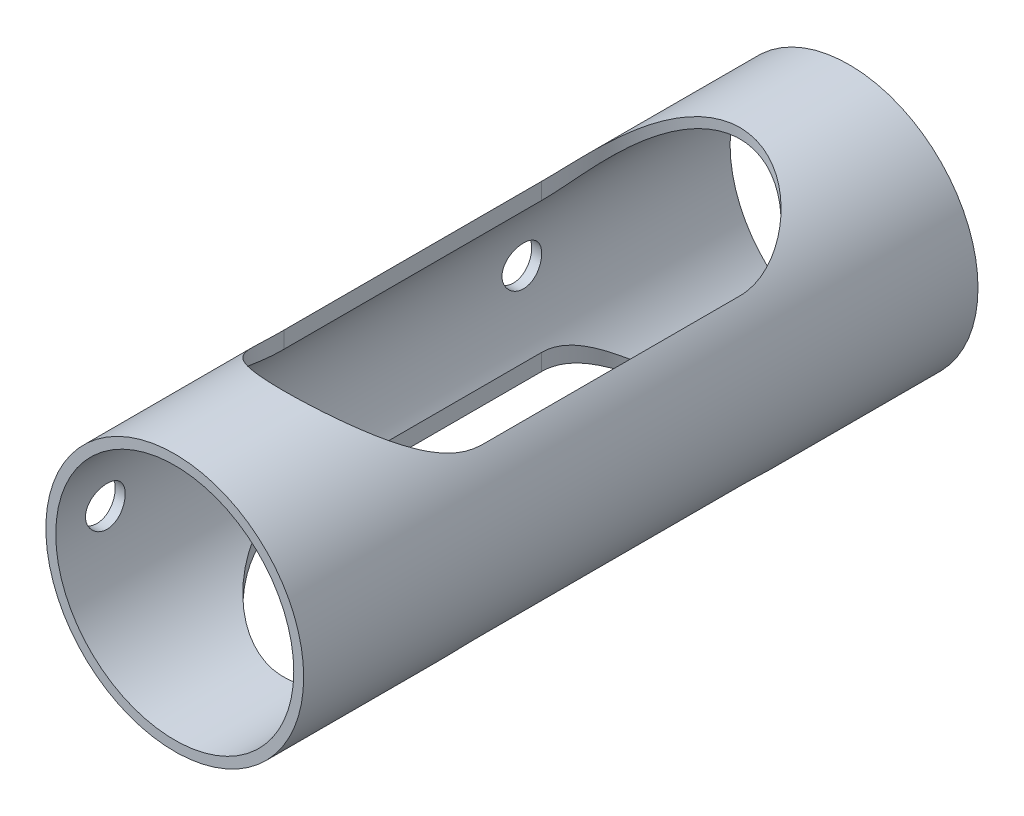
SolidWorks part; units mm, degrees
ref_plane "Front Plane" through (0, 0, 0) normal (0, 0, 1) x (1, 0, 0)
ref_plane "Top Plane" through (0, 0, 0) normal (0, 1, 0) x (1, 0, 0)
ref_plane "Right Plane" through (0, 0, 0) normal (1, 0, 0) x (0, 0, -1)
sketch "Sketch1" plane through (0, 0, 0) normal (0, 0, 1) x (1, 0, 0)
  circle A0 centre (0, 0) radius 13
  circle A1 centre (0, 0) radius 12
  dimension "D1" = 26
  dimension "D2" = 24
extrude "Boss-Extrude1" add sketch "Sketch1" along normal blind 68
sketch "Sketch2" plane through (0, 0, 0) normal (0, 1, 0) x (1, 0, 0)
  line L0 (0, -21) -> (0, -47) construction
  line L1 (10, -21) -> (10, -47)
  line L2 (-10, -21) -> (-10, -47)
  line L3 (13, 0) -> (-13, 0) construction
  arc A0 (10, -21) -> (-10, -21) centre (0, -21) ccw
  arc A1 (-10, -47) -> (10, -47) centre (0, -47) ccw
  point P3 (0, -34)
  dimension "D2" = 10
  dimension "D1" = 26
  dimension "D3" = 21
extrude "Cut-Extrude1" cut sketch "Sketch2" against normal mid plane 68
sketch "Sketch3" plane through (0, 0, 0) normal (1, 0, 0) x (0, 0, -1)
  circle A0 centre (-63, 0) radius 2
  circle A1 centre (-21, 0) radius 2
  point P4 (0, 0)
  dimension "D1" = 21
  dimension "D3" = 4
  dimension "D4" = 4
  dimension "D2" = 42
extrude "Cut-Extrude2" cut sketch "Sketch3" against normal blind 68
